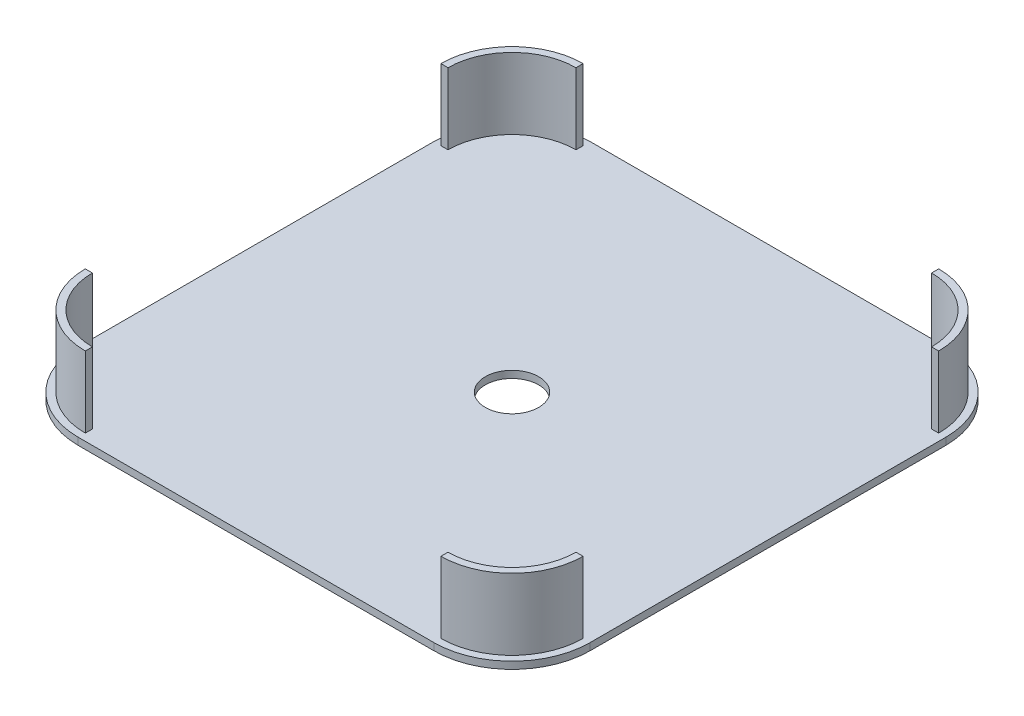
SolidWorks part; units mm, degrees
ref_plane "Plan de face" through (0, 0, 0) normal (0, 0, 1) x (1, 0, 0)
ref_plane "Plan de dessus" through (0, 0, 0) normal (0, 1, 0) x (1, 0, 0)
ref_plane "Plan de droite" through (0, 0, 0) normal (1, 0, 0) x (0, 0, -1)
sketch "Esquisse1" plane through (0, 0, 0) normal (0, 1, 0) x (1, 0, 0)
  line L1 (-56.6555, 33.1261) -> (43.3445, 33.1261)
  line L2 (-78.6555, 11.1261) -> (-78.6555, -88.8739)
  line L3 (-56.6555, -110.8739) -> (43.3445, -110.8739)
  line L4 (65.3445, 11.1261) -> (65.3445, -88.8739)
  arc A0 (43.3445, 33.1261) -> (65.3445, 11.1261) centre (43.3445, 11.1261) cw
  arc A1 (43.3445, -110.8739) -> (65.3445, -88.8739) centre (43.3445, -88.8739) ccw
  arc A2 (-78.6555, -88.8739) -> (-56.6555, -110.8739) centre (-56.6555, -88.8739) ccw
  arc A3 (-56.6555, 33.1261) -> (-78.6555, 11.1261) centre (-56.6555, 11.1261) ccw
  point P6 (65.3445, 33.1261)
  point P11 (-78.6555, -110.8739)
  point P14 (-78.6555, 33.1261)
  dimension "D3" = 22
  dimension "D4" = 22
  dimension "D5" = 22
  dimension "D6" = 22
  dimension "D1" = 144
  dimension "D2" = 144
extrude "Boss.-Extru.1" add sketch "Esquisse1" along normal blind 2
sketch "Esquisse3" plane through (0, 2, 0) normal (0, 1, 0) x (1, 0, 0)
  line L0 (43.3445, 31.1261) -> (43.3445, 29.1261)
  line L1 (61.3445, 11.1261) -> (63.3445, 11.1261)
  line L2 (43.3445, -106.8739) -> (43.3445, -108.8739)
  line L3 (61.3445, -88.8739) -> (63.3445, -88.8739)
  line L4 (-76.6555, -88.8739) -> (-74.6555, -88.8739)
  line L5 (-56.6555, -108.8739) -> (-56.6555, -106.8739)
  line L6 (-76.6555, 11.1261) -> (-74.6555, 11.1261)
  line L7 (-56.6555, 31.1261) -> (-56.6555, 29.1261)
  arc A7 (-56.6555, 31.1261) -> (-76.6555, 11.1261) centre (-56.6555, 11.1261) ccw
  arc A8 (-56.6555, 31.1261) -> (-76.6555, 11.1261) centre (-56.6555, 11.1261) ccw
  arc A21 (-76.6555, -88.8739) -> (-56.6555, -108.8739) centre (-56.6555, -88.8739) ccw
  arc A22 (-76.6555, -88.8739) -> (-56.6555, -108.8739) centre (-56.6555, -88.8739) ccw
  arc A24 (43.3445, -108.8739) -> (63.3445, -88.8739) centre (43.3445, -88.8739) ccw
  arc A25 (43.3445, -108.8739) -> (63.3445, -88.8739) centre (43.3445, -88.8739) ccw
  arc A26 (-56.6555, 29.1261) -> (-74.6555, 11.1261) centre (-56.6555, 11.1261) ccw
  arc A27 (63.3445, 11.1261) -> (43.3445, 31.1261) centre (43.3445, 11.1261) ccw
  arc A28 (63.3445, 11.1261) -> (43.3445, 31.1261) centre (43.3445, 11.1261) ccw
  arc A29 (61.3445, 11.1261) -> (43.3445, 29.1261) centre (43.3445, 11.1261) ccw
  arc A30 (-74.6555, -88.8739) -> (-56.6555, -106.8739) centre (-56.6555, -88.8739) ccw
  arc A33 (43.3445, -106.8739) -> (61.3445, -88.8739) centre (43.3445, -88.8739) ccw
  arc A34 (43.3445, -106.8739) -> (61.3445, -88.8739) centre (43.3445, -88.8739) ccw
  dimension "D1" = 2
  dimension "D2" = 2
  dimension "D3" = 2
  dimension "D4" = 2
  dimension "D5" = 2
  dimension "D6" = 2
  dimension "D7" = 2
  dimension "D8" = 4
extrude "Boss.-Extru.2" add sketch "Esquisse3" along normal blind 20
sketch "Esquisse4" plane through (0, 2, 0) normal (0, 1, 0) x (1, 0, 0)
  line L0 (43.3445, 33.1261) -> (-56.6555, 33.1261) construction
  line L1 (-78.6555, 11.1261) -> (-78.6555, -88.8739) construction
  circle A0 centre (-6.6555, -38.8739) radius 7.5
  point P6 (-17.9201, -36.475)
  dimension "D1" = 15
  dimension "D2" = 72
  dimension "D3" = 72
extrude "Enlèv. mat.-Extru.1" cut sketch "Esquisse4" against normal through all
